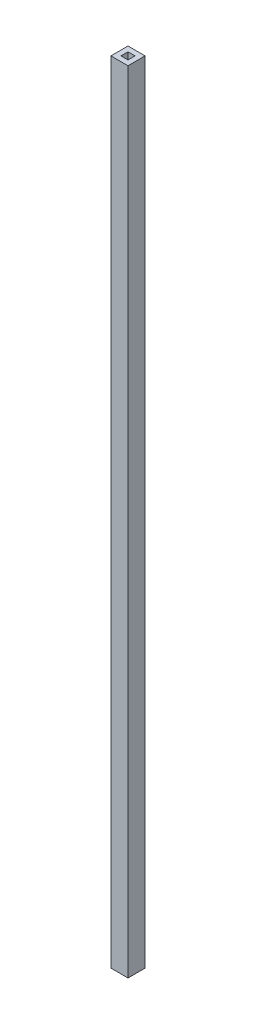
SolidWorks part; units mm, degrees
ref_plane "Front Plane" through (0, 0, 0) normal (0, 0, 1) x (1, 0, 0)
ref_plane "Top Plane" through (0, 0, 0) normal (0, 1, 0) x (1, 0, 0)
ref_plane "Right Plane" through (0, 0, 0) normal (1, 0, 0) x (0, 0, -1)
sketch "Sketch1" plane through (0, 0, 0) normal (0, 1, 0) x (1, 0, 0)
  line L1 (-25.4, 25.4) -> (25.4, 25.4)
  line L2 (-25.4, 25.4) -> (-25.4, -25.4)
  line L3 (-25.4, -25.4) -> (25.4, -25.4)
  line L4 (25.4, 25.4) -> (25.4, -25.4)
  line L5 (-25.4, 25.4) -> (25.4, -25.4) construction
  line L6 (-25.4, -25.4) -> (25.4, 25.4) construction
  line L7 (-10.4, 10.4) -> (10.4, 10.4)
  line L8 (-10.4, 10.4) -> (-10.4, -10.4)
  line L9 (-10.4, -10.4) -> (10.4, -10.4)
  line L10 (10.4, 10.4) -> (10.4, -10.4)
  line L11 (-10.4, 10.4) -> (10.4, -10.4) construction
  line L12 (-10.4, -10.4) -> (10.4, 10.4) construction
  point P0 (0, 0)
  point P6 (0, 0)
  dimension "D1" = 50.8
  dimension "D2" = 15
extrude "Boss-Extrude1" add sketch "Sketch1" along normal blind 2346.325
